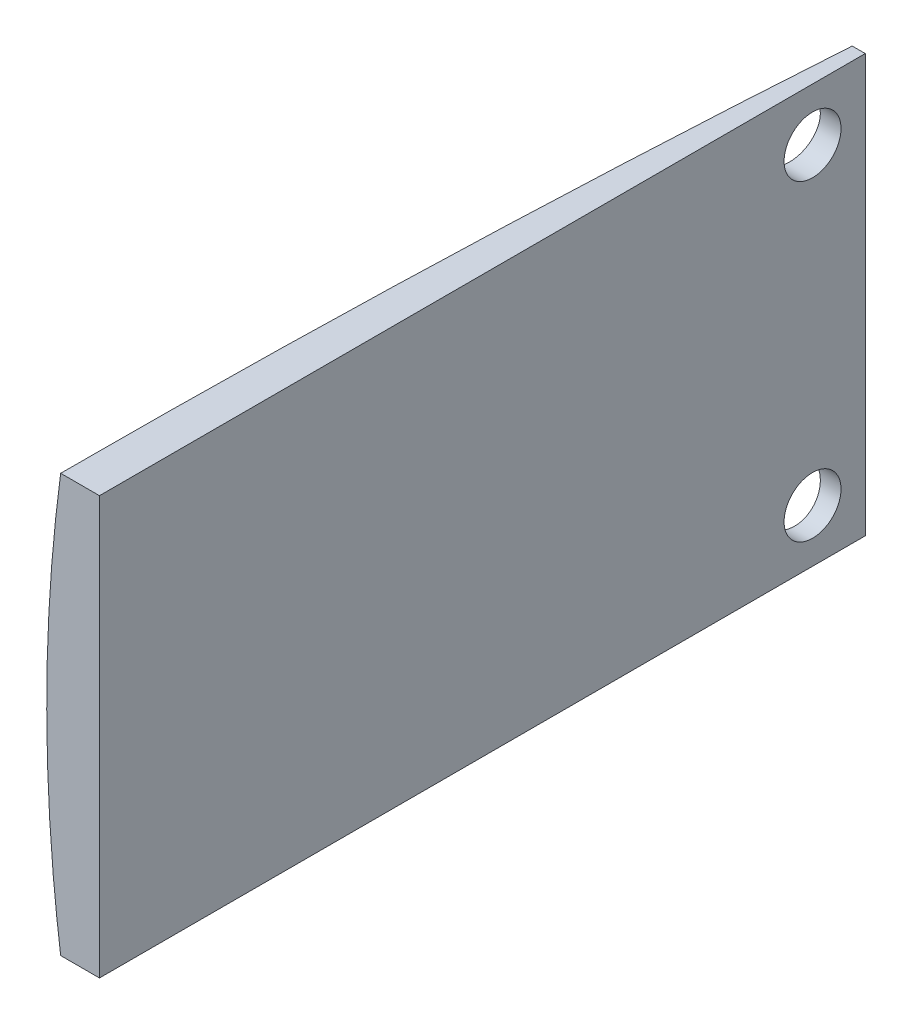
SolidWorks part; units mm, degrees
material "Nylon 101"
ref_plane "Front Plane" through (0, 0, 0) normal (0, 0, 1) x (1, 0, 0)
ref_plane "Top Plane" through (0, 0, 0) normal (0, 1, 0) x (1, 0, 0)
ref_plane "Right Plane" through (0, 0, 0) normal (1, 0, 0) x (0, 0, -1)
sketch "Sketch1" plane through (0, 0, 0) normal (0, 0, 1) x (1, 0, 0)
  line L0 (0, 0) -> (1372.87, 0) construction
  line L1 (1372.87, -509.27) -> (1372.87, 509.27)
  ellipse E0 centre (1372.87, 0) end of major axis (0, 0) minor radius 509.27 (1372.87, 509.27) -> (1372.87, -509.27) ccw
  point P4 (1372.87, 0)
  dimension "D1" = 1018.54
  dimension "D2" = 1372.87
revolve "Revolve1" add sketch "Sketch1" angle 360 about L1
sketch "Sketch2" plane through (0, 0, 0) normal (1, 0, 0) x (0, 0, -1)
  line L1 (92.202, 25.146) -> (-92.202, 25.146)
  line L2 (92.202, 25.146) -> (92.202, -25.146)
  line L3 (92.202, -25.146) -> (-92.202, -25.146)
  line L4 (-92.202, 25.146) -> (-92.202, -25.146)
  line L5 (92.202, 25.146) -> (-92.202, -25.146) construction
  line L6 (92.202, -25.146) -> (-92.202, 25.146) construction
  point P0 (0, 0)
  dimension "D1" = 184.404
  dimension "D2" = 50.292
extrude "Cut-Extrude2" cut sketch "Sketch2" against normal through all and the other way through all flip side to cut contours L1 L4 L3 L2
sketch "Sketch3" plane through (0, 0, 0) normal (1, 0, 0) x (0, 0, -1)
  line L1 (92.202, 25.146) -> (-92.202, 25.146)
  line L2 (92.202, 25.146) -> (92.202, -25.146)
  line L3 (92.202, -25.146) -> (-92.202, -25.146)
  line L4 (-92.202, 25.146) -> (-92.202, -25.146)
  line L5 (92.202, 25.146) -> (-92.202, -25.146) construction
  line L6 (92.202, -25.146) -> (-92.202, 25.146) construction
  point P0 (0, 0)
extrude "Cut-Extrude3" cut sketch "Sketch3" along normal through all from offset 6.35
sketch "Sketch4" plane through (6.35, 0, 0) normal (1, 0, 0) x (0, 0, -1)
  line L0 (92.202, 25.146) -> (-92.202, 25.146) construction
  line L1 (-92.202, 25.146) -> (-92.202, -25.146) construction
  line L2 (92.202, -25.146) -> (92.202, 25.146) construction
  line L3 (-92.202, -25.146) -> (92.202, -25.146) construction
  circle A0 centre (-85.852, 18.796) radius 3.429
  circle A1 centre (-85.852, -18.796) radius 3.429
  circle A2 centre (85.852, -18.796) radius 3.429
  circle A3 centre (85.852, 18.796) radius 3.429
  dimension "D1" = 6.35
  dimension "D5" = 6.858
  dimension "D2" = 6.35
  dimension "D3" = 6.35
  dimension "D4" = 6.35
extrude "Cut-Extrude4" cut sketch "Sketch4" against normal through all
sketch "Sketch5" plane through (0, 0, 0) normal (0, 0, 1) x (1, 0, 0)
  line L1 (-45.5632, -78.759) -> (23.5723, -78.759)
  line L2 (-45.5632, -78.759) -> (-45.5632, 28.6133)
  line L3 (-45.5632, 28.6133) -> (23.5723, 28.6133)
  line L4 (23.5723, -78.759) -> (23.5723, 28.6133)
  line L5 (-45.5632, -78.759) -> (23.5723, 28.6133) construction
  line L6 (-45.5632, 28.6133) -> (23.5723, -78.759) construction
  point P0 (-10.9955, -25.0729)
extrude "Cut-Extrude5" cut sketch "Sketch5" along normal through all contours L2 L3 L4 L1
